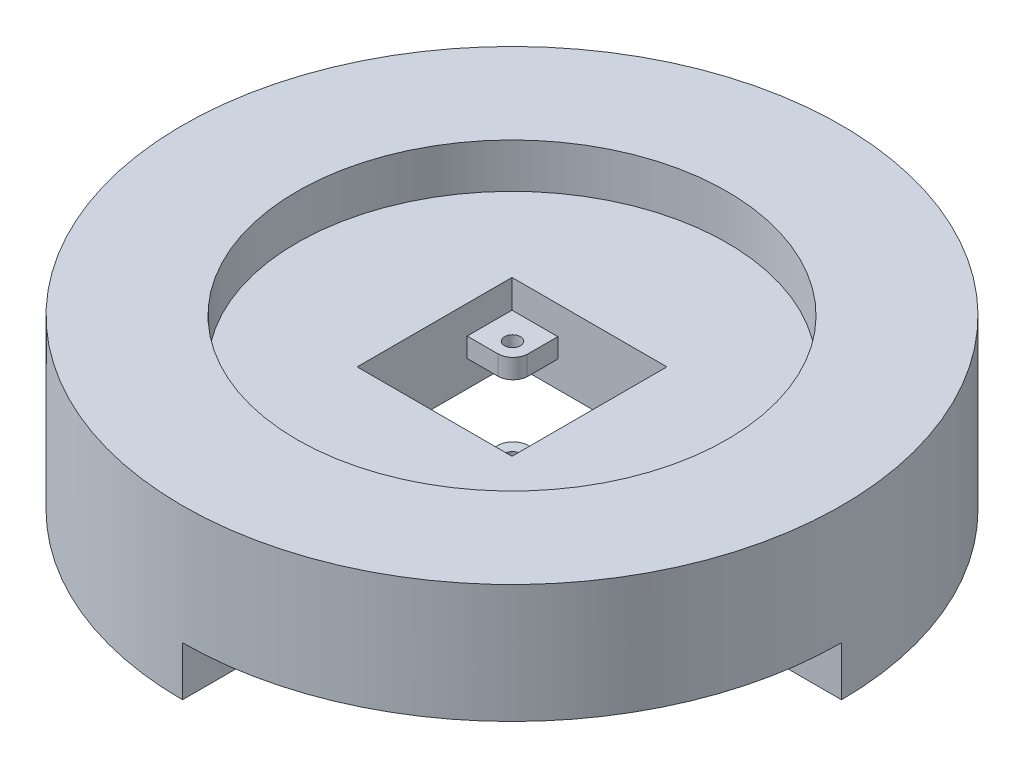
SolidWorks part; units mm, degrees
ref_plane "Front Plane" through (0, 0, 0) normal (0, 0, 1) x (1, 0, 0)
ref_plane "Top Plane" through (0, 0, 0) normal (0, 1, 0) x (1, 0, 0)
ref_plane "Right Plane" through (0, 0, 0) normal (1, 0, 0) x (0, 0, -1)
sketch "Sketch1" plane through (0, 0, 0) normal (0, 1, 0) x (1, 0, 0)
  circle A0 centre (0, 0) radius 50
  dimension "D1" = 100
extrude "Boss-Extrude1" add sketch "Sketch1" along normal blind 25
sketch "Sketch2" plane through (0, 25, 0) normal (0, 1, 0) x (1, 0, 0)
  circle A0 centre (0, 0) radius 32.625
  dimension "D1" = 65.25
extrude "Cut-Extrude1" cut sketch "Sketch2" against normal blind 6.75
sketch "Sketch3" plane through (0, 18.25, 0) normal (0, 1, 0) x (1, 0, 0)
  line L1 (11.75, 11.75) -> (-11.75, 11.75)
  line L2 (11.75, 11.75) -> (11.75, -11.75)
  line L3 (11.75, -11.75) -> (-11.75, -11.75)
  line L4 (-11.75, 11.75) -> (-11.75, -11.75)
  line L5 (11.75, 11.75) -> (-11.75, -11.75) construction
  line L6 (11.75, -11.75) -> (-11.75, 11.75) construction
  point P0 (0, 0)
  dimension "D1" = 23.5
  dimension "D2" = 23.5
extrude "Cut-Extrude2" cut sketch "Sketch3" against normal blind 4.3
sketch "Sketch4" plane through (0, 13.95, 0) normal (0, 1, 0) x (1, 0, 0)
  line L0 (-11.75, 4.95) -> (-7.1, 4.95)
  line L1 (-11.75, 11.75) -> (-11.75, -11.75) construction
  line L2 (-4.8, 7.1) -> (-4.8, 11.75)
  line L3 (11.75, 11.75) -> (-11.75, 11.75) construction
  line L4 (11.75, 11.75) -> (-11.75, -11.75) construction
  line L11 (7.1, -4.8) -> (11.75, -4.8)
  line L12 (4.95, -11.75) -> (4.95, -7.1)
  line L13 (-4.8, 11.75) -> (11.75, 11.75)
  line L14 (11.75, 11.75) -> (11.75, -4.8)
  line L15 (4.95, -11.75) -> (-11.75, -11.75)
  line L16 (-11.75, -11.75) -> (-11.75, 4.95)
  arc A2 (-4.8, 7.1) -> (-7.1, 4.95) centre (-7.1, 7.2552) cw
  arc A3 (7.1, -4.8) -> (4.95, -7.1) centre (7.2552, -7.1) ccw
  dimension "D1" = 6.95
  dimension "D4" = 4.65
  dimension "D2" = 6.8
extrude "Cut-Extrude3" cut sketch "Sketch4" against normal up to surface (13.95 mm away) up to face at (0, 0, 50)
sketch "Sketch12" plane through (0, 13.95, 0) normal (0, 1, 0) x (1, 0, 0)
  line L0 (-8.275, 11.75) -> (-8.275, 8.35) construction
  line L1 (-4.8, 11.75) -> (-11.75, 11.75) construction
  line L2 (-11.75, 8.35) -> (-8.275, 8.35) construction
  line L3 (-11.75, 11.75) -> (-11.75, 4.95) construction
  line L4 (-8.275, 8.35) -> (-7.6386, 7.7136) construction
  line L5 (-11.75, -11.75) -> (11.75, 11.75) construction
  line L6 (11.75, 11.75) -> (-11.75, 11.75) construction
  line L7 (8.35, -8.275) -> (7.7136, -7.6386) construction
  line L8 (8.35, -11.75) -> (8.35, -8.275) construction
  line L9 (11.75, -8.275) -> (8.35, -8.275) construction
  line L10 (-11.75, -11.75) -> (11.75, -11.75) construction
  point P8 (-7.6386, 7.7136)
  point P17 (7.7136, -7.6386)
  dimension "D1" = 0.9
  dimension "D2" = 45
sketch "Sketch24" plane through (0, 0, 0) normal (0, -1, 0) x (1, 0, 0)
  line L1 (-11.75, 11.75) -> (11.75, 11.75)
  line L2 (-11.75, 11.75) -> (-11.75, -11.75)
  line L3 (-11.75, -11.75) -> (11.75, -11.75)
  line L4 (11.75, 11.75) -> (11.75, -11.75)
extrude "Cut-Extrude4" cut sketch "Sketch24" against normal blind 11
sketch "Sketch25" plane through (0, 0, 0) normal (0, -1, 0) x (1, 0, 0)
  circle A0 centre (0, 0) radius 50
  circle A1 centre (0, 0) radius 50 construction
extrude "Cut-Extrude5" cut sketch "Sketch25" against normal blind 7
sketch "Sketch26" plane through (0, 13.95, 0) normal (0, 1, 0) x (1, 0, 0)
  circle A0 centre (-7.6386, 7.7136) radius 1.2
  circle A1 centre (7.7136, -7.6386) radius 1.2
  dimension "D1" = 2.4
extrude "Cut-Extrude6" cut sketch "Sketch26" against normal through all
sketch "Sketch27" plane through (0, 7, 0) normal (0, -1, 0) x (1, 0, 0)
  line L0 (-11.75, 11.75) -> (11.75, -11.75) construction
  line L1 (-50, 0) -> (-40, 0)
  line L2 (0, 50) -> (0, 40)
  line L3 (40, 0) -> (50, 0)
  line L4 (0, -40) -> (0, -50)
  arc A0 (0, -50) -> (50, 0) centre (0, 0) ccw
  arc A3 (0, -40) -> (40, 0) centre (0, 0) ccw
  circle A4 centre (0, 0) radius 40 construction
  circle A5 centre (0, 0) radius 50 construction
  arc A6 (0, 40) -> (-40, 0) centre (0, 0) ccw
  arc A7 (0, 50) -> (-50, 0) centre (0, 0) ccw
  circle A8 centre (0, 0) radius 50 construction
  point P1 (0, 0)
  dimension "D1" = 10
extrude "Boss-Extrude2" add sketch "Sketch27" along normal blind 7.5
